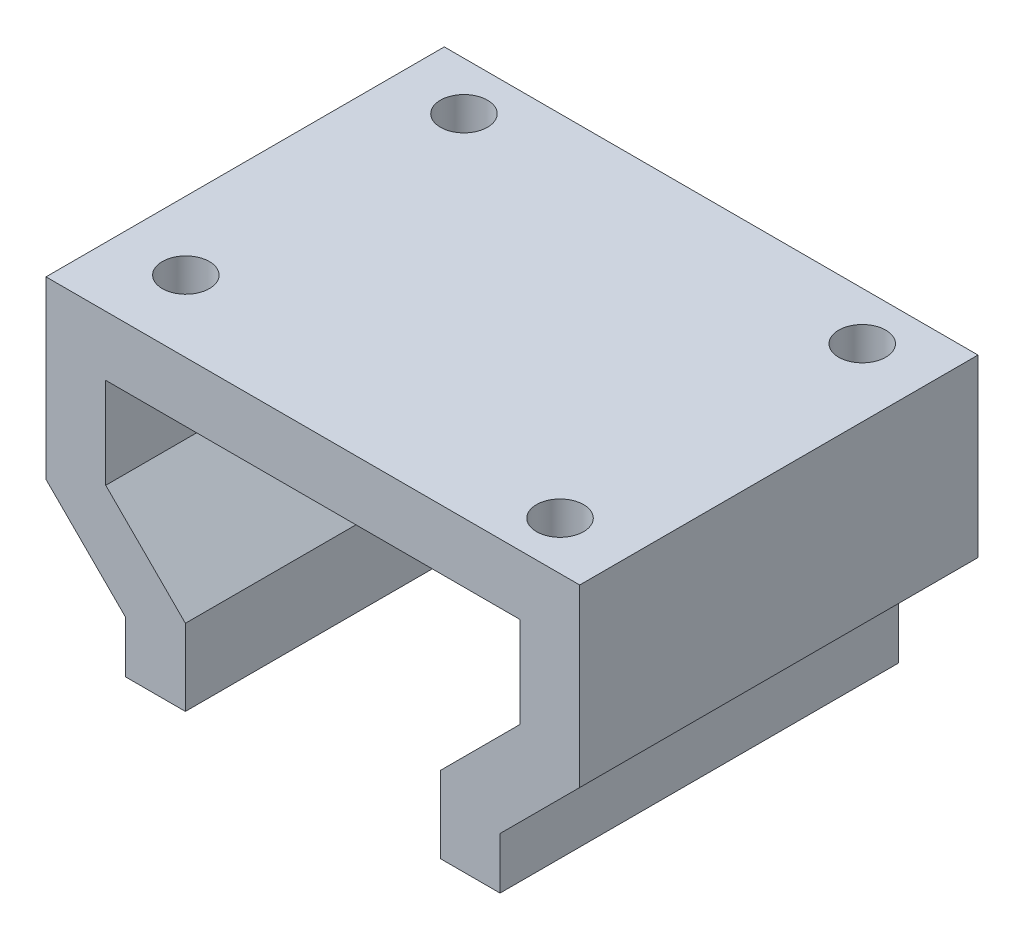
SolidWorks part; units mm, degrees
ref_plane "Front Plane" through (0, 0, 0) normal (0, 0, 1) x (1, 0, 0)
ref_plane "Top Plane" through (0, 0, 0) normal (0, 1, 0) x (1, 0, 0)
ref_plane "Right Plane" through (0, 0, 0) normal (1, 0, 0) x (0, 0, -1)
sketch "Sketch1" plane through (0, 0, 0) normal (0, 0, 1) x (1, 0, 0)
  line L0 (12.7, 12.7) -> (-12.7, 12.7) construction
  line L1 (-12.7, 12.7) -> (-12.7, 7.62) construction
  line L2 (-12.7, 7.62) -> (-7.62, 2.54) construction
  line L3 (-7.62, 2.54) -> (-7.62, -2.54) construction
  line L7 (0, 12.7) -> (0, -2.54) construction
  line L10 (7.62, 2.54) -> (7.62, -2.54) construction
  line L11 (12.7, 7.62) -> (7.62, 2.54) construction
  line L12 (12.7, 12.7) -> (12.7, 7.62) construction
  line L13 (13.208, 13.208) -> (-13.208, 13.208)
  line L14 (-13.208, 13.208) -> (-13.208, 7.4096)
  line L15 (-13.208, 7.4096) -> (-8.128, 2.3296)
  line L16 (-8.128, 2.3296) -> (-8.128, -2.54)
  line L22 (8.128, 2.3296) -> (8.128, -2.54)
  line L23 (13.208, 7.4096) -> (8.128, 2.3296)
  line L24 (13.208, 13.208) -> (13.208, 7.4096)
  line L25 (-0.508, 12.7) -> (-0.508, -2.54)
  line L26 (-17.018, 17.018) -> (-17.018, 5.8314)
  line L27 (-17.018, 5.8314) -> (-11.938, 0.7514)
  line L28 (-11.938, 0.7514) -> (-11.938, -2.54)
  line L34 (11.938, 0.7514) -> (11.938, -2.54)
  line L35 (17.018, 5.8314) -> (11.938, 0.7514)
  line L36 (17.018, 17.018) -> (17.018, 5.8314)
  line L37 (17.018, 17.018) -> (-17.018, 17.018)
  line L38 (-11.938, -2.54) -> (11.938, -2.54)
  line L39 (-12.7, -14.4886) -> (12.7, -14.4886) construction
  line L40 (-11.938, -2.54) -> (-17.018, -7.62) construction
  line L41 (-8.128, -4.1182) -> (-13.208, -9.1982) construction
  line L42 (-7.62, -4.3286) -> (-12.7, -9.4086) construction
  line L43 (-12.7, -9.4086) -> (-12.7, -14.4886) construction
  line L44 (-13.208, -9.1982) -> (-13.208, -14.9966) construction
  line L45 (-17.018, -7.62) -> (-17.018, -18.8066) construction
  line L46 (-13.208, -14.9966) -> (13.208, -14.9966) construction
  line L47 (-17.018, -18.8066) -> (17.018, -18.8066) construction
  line L48 (-0.508, 12.7) -> (-0.508, -12.7) construction
  line L49 (0, 12.7) -> (0, -12.7) construction
  line L50 (12.7, -9.4086) -> (12.7, -14.4886) construction
  line L51 (13.208, -9.1982) -> (13.208, -14.9966) construction
  line L52 (11.938, -2.54) -> (17.018, -7.62) construction
  line L53 (8.128, -4.1182) -> (13.208, -9.1982) construction
  line L54 (7.62, -4.3286) -> (12.7, -9.4086) construction
  line L55 (17.018, -7.62) -> (17.018, -18.8066) construction
  line L56 (8.128, 2.3296) -> (8.128, -4.1182) construction
  line L57 (7.62, 2.54) -> (7.62, -4.3286) construction
  line L58 (-7.62, 2.54) -> (-7.62, -4.3286) construction
  line L59 (-8.128, 2.3296) -> (-8.128, -4.1182) construction
  point P9 (-7.62, 0)
  dimension "D1" = 12.7
  dimension "D2" = 0.508
  dimension "D4" = 5.08
  dimension "D6" = 5.08
  dimension "D8" = 3.81
extrude "Boss-Extrude1" add sketch "Sketch1" along normal blind 25.4 contours L28 L38 L16 L15 L14 L13 L24 L23 L22 L34 L35 L36 L37 L26 L27
sketch "Sketch2" plane through (0, 17.018, 0) normal (0, 1, 0) x (1, 0, 0)
  line L0 (-12.7, -3.064) -> (12.7, -3.064) construction
  line L1 (12.7, -3.064) -> (12.7, -22.336) construction
  line L2 (17.018, -25.4) -> (17.018, 0) construction
  circle A0 centre (-12.7, -3.064) radius 1.5
  circle A1 centre (-12.6561, -20.844) radius 1.5
  circle A2 centre (12.7, -22.336) radius 1.5
  circle A3 centre (12.7, -3.064) radius 1.5
  point P8 (0, -3.064)
  point P12 (17.018, -12.7)
  point P13 (12.7, -12.7)
  dimension "D1" = 3
  dimension "D2" = 3
  dimension "D3" = 3
  dimension "D4" = 3
  dimension "D5" = 25.4
  dimension "D6" = 25.4
  dimension "D7" = 17.78
extrude "Cut-Extrude1" cut sketch "Sketch2" against normal blind 3.81
